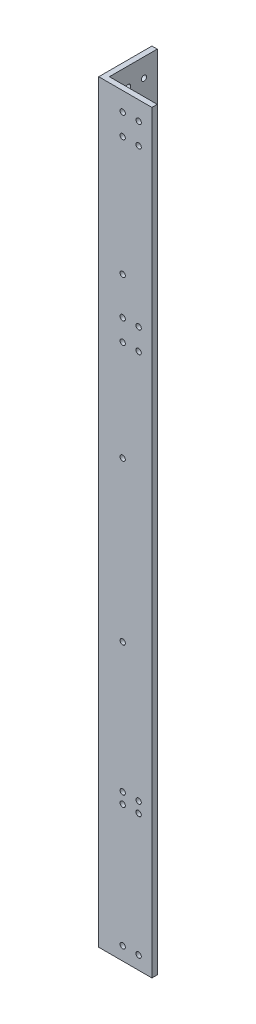
SolidWorks part; units mm, degrees
ref_plane "Front Plane" through (0, 0, 0) normal (0, 0, 1) x (1, 0, 0)
ref_plane "Top Plane" through (0, 0, 0) normal (0, 1, 0) x (1, 0, 0)
ref_plane "Right Plane" through (0, 0, 0) normal (1, 0, 0) x (0, 0, -1)
sketch "Sketch2" plane through (0, 0, 0) normal (0, 1, 0) x (1, 0, 0)
  line L0 (0, 31.75) -> (3.175, 31.75)
  line L1 (3.175, 31.75) -> (3.175, 3.175)
  line L2 (3.175, 3.175) -> (31.75, 3.175)
  line L3 (31.75, 3.175) -> (31.75, 0)
  line L4 (31.75, 0) -> (0, 0)
  line L5 (0, 0) -> (0, 31.75)
  point P9 (1.5875, 31.75)
  point P10 (31.75, 1.5875)
  dimension "D4" = 3.175
  dimension "D1" = 31.75
  dimension "D2" = 31.75
  dimension "D3" = 3.175
extrude "Boss-Extrude1" add sketch "Sketch2" along normal blind 450
sketch "LeftSideHoles-Sketch3" plane through (0, 0, 0) normal (0, 0, 1) x (1, 0, 0)
  line L0 (0, 0) -> (31.75, 0) construction
  line L3 (0, 450) -> (0, 0) construction
  circle A0 centre (14.2875, 81.1125) radius 1.5875
  circle A1 centre (23.8125, 81.1125) radius 1.5875
  circle A2 centre (14.2875, 87.4625) radius 1.5875
  circle A3 centre (23.8125, 87.4625) radius 1.5875
  circle A4 centre (14.2875, 438.8875) radius 1.5875
  circle A5 centre (14.2875, 426.1875) radius 1.5875
  circle A6 centre (23.8125, 438.8875) radius 1.5875
  circle A7 centre (23.8125, 426.1875) radius 1.5875
  circle A10 centre (14.2875, 332.6026) radius 1.5875
  circle A11 centre (23.8125, 332.6026) radius 1.5875
  circle A12 centre (14.2875, 319.9026) radius 1.5875
  circle A13 centre (23.8125, 319.9026) radius 1.5875
  circle A14 centre (14.2875, 7.9375) radius 1.5875
  circle A15 centre (23.8125, 7.9375) radius 1.5875
  circle A16 centre (14.2875, 165) radius 1.5875
  circle A17 centre (14.2875, 260) radius 1.5875
  circle A18 centre (14.2875, 355) radius 1.5875
  point P24 (15.875, 0)
  dimension "D4" = 3.175
  dimension "D1" = 81.1125
  dimension "D2" = 14.2875
  dimension "D8" = 11.1125
  dimension "D10" = 7.9375
  dimension "D5" = 6.35
  dimension "D7" = 12.7
  dimension "D9" = 12.7
  dimension "D3" = 9.525
  dimension "D11" = 332.6026
  dimension "D12" = 165
  dimension "D13" = 95
  dimension "D14" = 95
sketch "BackSideHoles-Sketch4" plane through (0, 0, 0) normal (-1, 0, 0) x (0, 0, 1)
  line L0 (-31.75, 450) -> (0, 450) construction
  line L1 (0, 450) -> (0, 0) construction
  line L3 (-31.75, 0) -> (0, 0) construction
  circle A0 centre (-23.8125, 81.1125) radius 1.5875
  circle A1 centre (-14.2875, 81.1125) radius 1.5875
  circle A2 centre (-23.8125, 87.4625) radius 1.5875
  circle A3 centre (-14.2875, 87.4625) radius 1.5875
  circle A4 centre (-23.8125, 438.8875) radius 1.5875
  circle A5 centre (-14.2875, 438.8875) radius 1.5875
  circle A6 centre (-23.8125, 426.1875) radius 1.5875
  circle A7 centre (-14.2875, 426.1875) radius 1.5875
  circle A10 centre (-23.8125, 332.6026) radius 1.5875
  circle A11 centre (-14.2875, 332.6026) radius 1.5875
  circle A12 centre (-23.8125, 326.2526) radius 1.5875
  circle A13 centre (-14.2875, 326.2526) radius 1.5875
  circle A14 centre (-14.2875, 165) radius 1.5875
  circle A15 centre (-14.2875, 260) radius 1.5875
  circle A16 centre (-14.2875, 355) radius 1.5875
  dimension "D4" = 3.175
  dimension "D2" = 14.2875
  dimension "D5" = 6.35
  dimension "D7" = 12.7
  dimension "D3" = 81.1125
  dimension "D6" = 11.1125
  dimension "D8" = 6.35
  dimension "D9" = 9.525
  dimension "D1" = 332.6026
  dimension "D10" = 165
  dimension "D11" = 95
  dimension "D12" = 95
extrude "LeftSideHoles-Cut-Extrude1" cut sketch "LeftSideHoles-Sketch3" against normal blind 3.175
extrude "BackSideHoles-Cut-Extrude2" cut sketch "BackSideHoles-Sketch4" against normal blind 3.175
equation "\"RailThickness\"= .125in'Spec"
equation "\"VSWidth\"= 1.25in'Spec"
equation "\"VSHeight\"= 1.25in'Spec"
equation "\"VSLength\"= 450mm"
equation "\"HoleOffsetFromEdge\"= \"RailThickness\" * 2.5"
equation "\"HoleOffsetFromSide\"= \"RailThickness\" * 3.5"
equation "\"LegHeight\"= 70mm'Space needed for PSU/Stepper/Electronics"
equation "\"VSBottomSideRailHoleY1FromBottomOfLowerRail\"= \"V1 BottomOfLowerRail\" + \"HoleOffsetFromSide\"'Equals 70.1125"
equation "\"VSSideRailHoleX1FromSide\"= \"HoleOffsetFromSide\" + \"RailThickness\""
equation "\"FasteningHoleDiameter\"= .125in"
equation "\"VSBottomSideRailHoleY2FromY1\"= \"LowerRailHeight\" - \"HoleOffsetFromSide\" - \"HoleOffsetFromEdge\"'Equals 6.35"
equation "\"VSTopSideRailHoleY1FromEdge\"= \"HoleOffsetFromEdge\" + \"RailThickness\""
equation "\"D4@LeftSideHoles-Sketch3\"=\"FasteningHoleDiameter\""
equation "\"D1@LeftSideHoles-Sketch3\"=\"VSBottomSideRailHoleY1FromBottomOfLowerRail\""
equation "\"D2@LeftSideHoles-Sketch3\"=\"VSSideRailHoleX1FromSide\""
equation "\"D1@Boss-Extrude1\"=\"VSLength\""
equation "\"D4@BackSideHoles-Sketch4\" = \"FasteningHoleDiameter\""
equation "\"D3@BackSideHoles-Sketch4\"=\"VSBottomSideRailHoleY1FromBottomOfLowerRail\""
equation "\"D2@BackSideHoles-Sketch4\" = \"VSSideRailHoleX1FromSide\""
equation "\"D8@LeftSideHoles-Sketch3\"=\"VSTopSideRailHoleY1FromEdge\""
equation "\"VSMidSideRailHoleY1FromV8TopOfMidSideRail\"= \"V8 ToTopOfMidSideRail\" - \"HoleOffsetFromEdge\"'Equals 308.2875"
equation "\"LowerRailHeight\"= 1.00in"
equation "\"D1@Sketch2\"=\"VSHeight\""
equation "\"D2@Sketch2\"=\"VSWidth\""
equation "\"MidBackRailHeight\"= 1.00in"
equation "\"VSMidBackRailHoleY1FromV7TopOfMidBackRail\"= \"V7 ToTopOfMidBackRail\" - \"HoleOffsetFromSide\"'Equals 308.2875"
equation "\"TopRailHeight\"= 1.25in"
equation "\"MidSideRailHeight\"= 1.25in"
equation "\"D10@LeftSideHoles-Sketch3\"=\"HoleOffsetFromEdge\""
equation "\"D5@LeftSideHoles-Sketch3\"=\"VSBottomSideRailHoleY2FromY1\""
equation "\"D5@BackSideHoles-Sketch4\"=\"VSBottomSideRailHoleY2FromY1\""
equation "\"VSMidBackRailHoleY2FromY1\"= \"MidBackRailHeight\" - \"HoleOffsetFromSide\" - \"HoleOffsetFromEdge\"'Equals 6.35"
equation "\"VSMidSideRailHoleY2FromY1\"= \"MidSideRailHeight\" - \"HoleOffsetFromSide\" - \"HoleOffsetFromEdge\"'Equals 12.7"
equation "\"D7@LeftSideHoles-Sketch3\"=\"VSMidSideRailHoleY2FromY1\""
equation "\"D8@BackSideHoles-Sketch4\"=\"VSMidBackRailHoleY2FromY1\""
equation "\"D6@BackSideHoles-Sketch4\"=\"VSTopSideRailHoleY1FromEdge\""
equation "\"VSTopSideRailHoleY2FromY1\"= \"TopRailHeight\" - \"VSTopSideRailHoleY1FromEdge\" - \"HoleOffsetFromEdge\"'Equals 12.7"
equation "\"D7@BackSideHoles-Sketch4\"=\"VSTopSideRailHoleY2FromY1\""
equation "\"D9@LeftSideHoles-Sketch3\"=\"VSTopSideRailHoleY2FromY1\""
equation "\"VSBottomSideRailHoleX2FromX1\"= \"VSWidth\" - \"VSSideRailHoleX1FromSide\" - \"HoleOffsetFromEdge\""
equation "\"D3@LeftSideHoles-Sketch3\"=\"VSBottomSideRailHoleX2FromX1\""
equation "\"D9@BackSideHoles-Sketch4\"=\"VSBottomSideRailHoleX2FromX1\""
equation "\"V1 BottomOfLowerRail\"= \"LegHeight\""
equation "\"StepperShaftLength\"= 24mm'Pulley will be attached to the end"
equation "\"ZAxisLeadScrewLength\"= 200mm"
equation "\"LM8UUHeight\"= 24mm'Spec"
equation "\"V2 ToBedAtTopOfZAxis\"= \"V1 BottomOfLowerRail\" + \"StepperShaftLength\" + \"ZAxisLeadScrewLength\" - \"LM8UUHeight\" / 2"
equation "\"HotEndToTopOfXAxisGB\"= 63.315144mm'Measured from the100.Should be 63.315144"
equation "\"TopOfGBToBottomOfLinearRail\"= \"LinearGBWidth\" / 2 + \"LinearRailWidth\" / 2"
equation "\"LinearGBWidth\"= 27mm'Spec"
equation "\"V5 ToBottomOfXAxisLinearRail\"= \"V4 ToTopOfBuildPlate/HotEndTip\" + \"HotEndToTopOfXAxisGB\" - \"TopOfGBToBottomOfLinearRail\""
equation "\"LinearRailWidth\"= 12mm'Spec"
equation "\"V6 ToBottomOfGantryPulley\"= \"V5 ToBottomOfXAxisLinearRail\" - \"DistanceFromGABTopToLowerPulley\""
equation "\"GABUpperHeight\"= 6mm"
equation "\"GABMidWallHeight\"= 28mm'Must equal 28 or changes alignment"
equation "\"20TGT2PulleyWidth\"= 8.7mm'The STL of the Pulley in the diagram is a bit larger"
equation "\"GABMidShortRiserHeight\"= \"GABMidWallHeight\" / 2 - \"20TGT2PulleyWidth\"'Equals 5.3"
equation "\"GABRiserBossOffset\"= 0.8mm'Aligns Pulleys"
equation "\"DistanceFromGABTopToLowerPulley\"= \"GABUpperHeight\" + \"GABMidWallHeight\" - \"GABMidShortRiserHeight\" + \"GABRiserBossOffset\" / 2"
equation "\"V7 ToTopOfMidBackRail\"= \"V6 ToBottomOfGantryPulley\" + \"StepperShaftLength\""
equation "\"D1@BackSideHoles-Sketch4\" = \"VSMidBackRailHoleY1FromV7TopOfMidBackRail\""
equation "\"D11@LeftSideHoles-Sketch3\"=\"VSMidSideRailHoleY1FromV8TopOfMidSideRail\""
equation "\"V4 ToTopOfBuildPlate/HotEndTip\"= \"V2 ToBedAtTopOfZAxis\" + \"BedToBuildPlateStandoffLength\" + \"BuildPlateHeight\""
equation "\"BedToBuildPlateStandoffLength\"= 15mm"
equation "\"BuildPlateHeight\"= 8mm'Spec"
equation "\"V8 ToTopOfMidSideRail\"= \"V7 ToTopOfMidBackRail\" - \"RailThickness\""
equation "\"VSEnclosureOffsets\"= ( \"VSLength\" - \"LegHeight\" ) / 4"
equation "\"D12@LeftSideHoles-Sketch3\"=\"LegHeight\" + \"VSEnclosureOffsets\""
equation "\"D13@LeftSideHoles-Sketch3\"=\"VSEnclosureOffsets\""
equation "\"D14@LeftSideHoles-Sketch3\"=\"VSEnclosureOffsets\""
equation "\"D10@BackSideHoles-Sketch4\"=\"LegHeight\" + \"VSEnclosureOffsets\""
equation "\"D11@BackSideHoles-Sketch4\"=\"VSEnclosureOffsets\""
equation "\"D12@BackSideHoles-Sketch4\"=\"VSEnclosureOffsets\""
